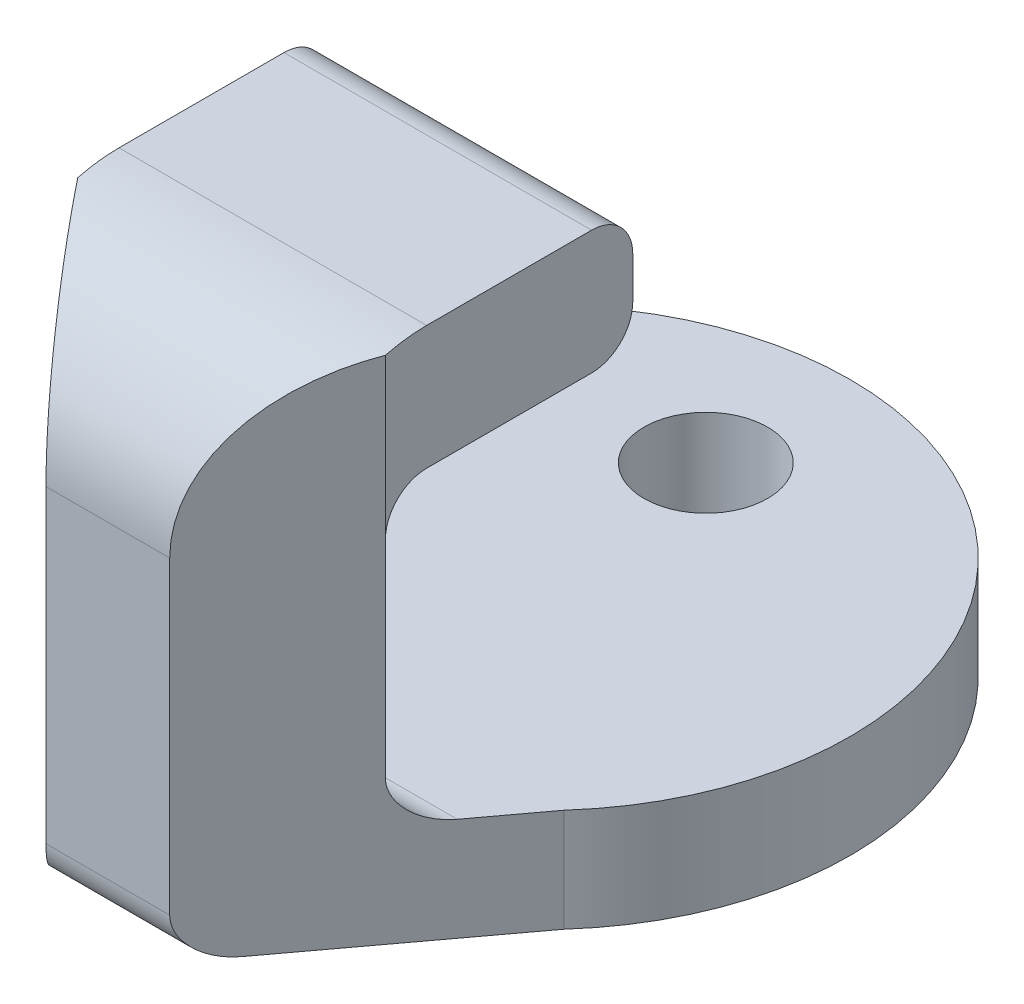
SolidWorks part; units mm, degrees
ref_plane "Front Plane" through (0, 0, 0) normal (0, 0, 1) x (1, 0, 0)
ref_plane "Top Plane" through (0, 0, 0) normal (0, 1, 0) x (1, 0, 0)
ref_plane "Right Plane" through (0, 0, 0) normal (1, 0, 0) x (0, 0, -1)
sketch "Sketch1" plane through (0, 0, 0) normal (0, 1, 0) x (1, 0, 0)
  line L0 (0, 0) -> (0, -15) construction
  line L1 (-3, -6) -> (3, -6)
  line L2 (-3, -6) -> (-3, -21)
  line L3 (-3, -21) -> (3, -21)
  line L4 (3, -6) -> (3, -21)
  line L5 (3, -21) -> (11.1583, -10.0246)
  line L6 (11.1583, -10.0246) -> (-11.1583, -10.0246) construction
  line L7 (-11.1583, -10.0246) -> (-3, -21)
  circle A0 centre (0, 0) radius 15
  circle A1 centre (0, 8) radius 3
  point P9 (0, -6)
  dimension "D1" = 8
  dimension "D5" = 6
  dimension "D2" = 15
  dimension "D3" = 6
  dimension "D4" = 6
extrude "Boss-Extrude2" add sketch "Sketch1" along normal blind 5 contours A0 L7 L2 | L4 A0 L2 L1 A1 | L2 A0 L4 L1 | A0 L2 L3 L4 | A0 L4 L5
sketch "Sketch2" plane through (0, 5, 0) normal (0, 1, 0) x (1, 0, 0)
  line L0 (3, -21) -> (7.4599, -15)
  line L1 (-3, -21) -> (3, -21)
  line L2 (-3, -21) -> (-3, -15)
  line L3 (-3, -15) -> (3, -15)
  line L4 (3, -21) -> (3, -15)
  line L5 (3, -21) -> (11.1583, -10.0246) construction
  line L6 (7.4599, -15) -> (3, -15)
  line L7 (-3, -21) -> (-7.4599, -15)
  line L8 (-11.1583, -10.0246) -> (-3, -21) construction
  line L9 (-7.4599, -15) -> (-3, -15)
  line M1 (3, -21) -> (11.1583, -10.0246)
  line M3 (-11.1583, -10.0246) -> (-3, -21)
  line M4 (-3, -21) -> (3, -21)
  dimension "D1" = 6
  dimension "D2" = 6
extrude "Boss-Extrude5" add sketch "Sketch2" along normal blind 20 contours L9 L2 M3 | L4 L3 L2 M4 | L6 L4 M1
sketch "Sketch6" plane through (0, 0, 15) normal (0, 0, -1) x (-1, 0, 0)
  line L0 (7.4599, 25) -> (7.4599, 5) construction
  line L1 (-7.4599, 25) -> (7.4599, 25)
  line L2 (-7.4599, 25) -> (-7.4599, 19)
  line L3 (-7.4599, 19) -> (7.4599, 19)
  line L4 (7.4599, 25) -> (7.4599, 19)
  dimension "D1" = 6
extrude "Boss-Extrude6" add sketch "Sketch6" along normal blind 12
fillet "Fillet2" radius 8 1 edges at (0, 25, 21)
fillet "Fillet3" radius 2 1 edges
fillet "Fillet4" radius 2 1 edges at (0, 19, 15)
fillet "Fillet5" radius 2 1 edges at (0, 0, 21)
fillet "Fillet6" radius 2 2 edges at (0, 25, 3) (0, 19, 3)
